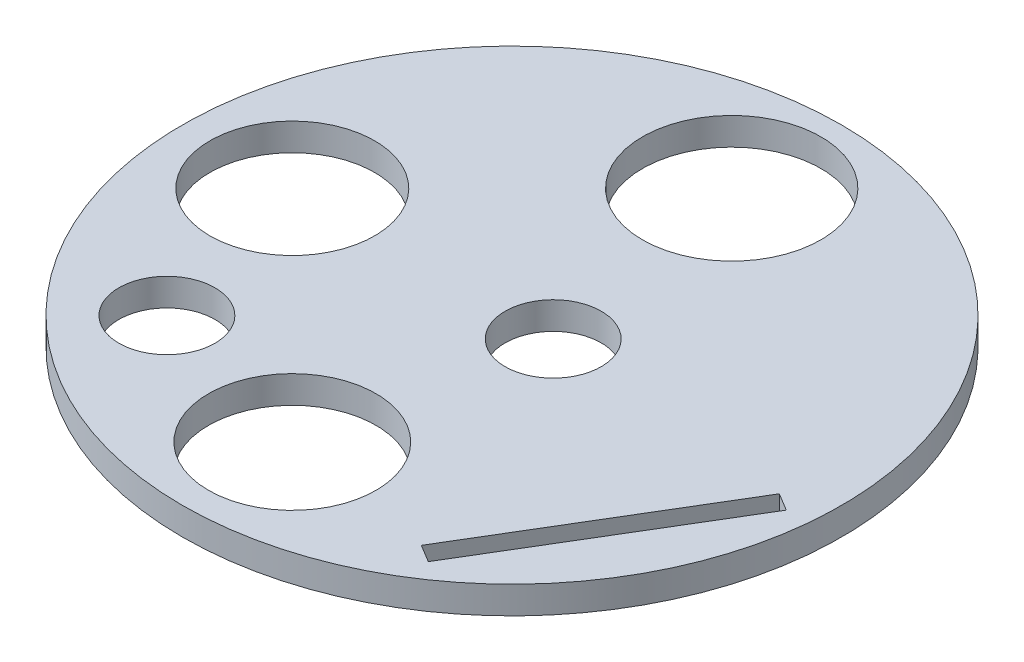
SolidWorks part; units mm, degrees
material "Acrylique (impact moyen-haut)"
ref_plane "Plan de face" through (0, 0, 0) normal (0, 0, 1) x (1, 0, 0)
ref_plane "Plan de dessus" through (0, 0, 0) normal (0, 1, 0) x (1, 0, 0)
ref_plane "Plan de droite" through (0, 0, 0) normal (1, 0, 0) x (0, 0, -1)
sketch "Esquisse1" plane through (0, 0, 0) normal (0, 1, 0) x (1, 0, 0)
  line L0 (0, 0) -> (3, 0) construction
  line L5 (3, 0) -> (-12.5429, -12.5864) construction
  line L6 (-16, 0) -> (0, 0) construction
  line L7 (21, -1.5351) -> (11.2143, -17.8212)
  line L8 (11.2143, -17.8212) -> (12.5, -18.5938)
  line L9 (12.5, -18.5938) -> (22.2858, -2.3076)
  line L10 (22.2858, -2.3076) -> (21, -1.5351)
  circle A0 centre (0, 0) radius 24
  circle A1 centre (0, 16) radius 6.5
  circle A2 centre (-16, 0) radius 6
  circle A3 centre (0, -16) radius 6.1
  circle A4 centre (-12.5429, -12.5864) radius 3.5
  circle A5 centre (0, 0) radius 16 construction
  circle A7 centre (3, 0) radius 3.5
  circle A8 centre (0, 0) radius 18.7911 construction
  point P16 (16.1071, -9.6781)
  dimension "D1" = 48
  dimension "D2" = 13
  dimension "D3" = 12
  dimension "D4" = 12.2
  dimension "D5" = 7
  dimension "D6" = 32
  dimension "D7" = 7
  dimension "D8" = 3
  dimension "D9" = 20
  dimension "D10" = 19
  dimension "D11" = 39
  dimension "D12" = 1.5
  dimension "D14" = 20
  dimension "D15" = 18
extrude "Boss.-Extru.1" add sketch "Esquisse1" along normal blind 2
